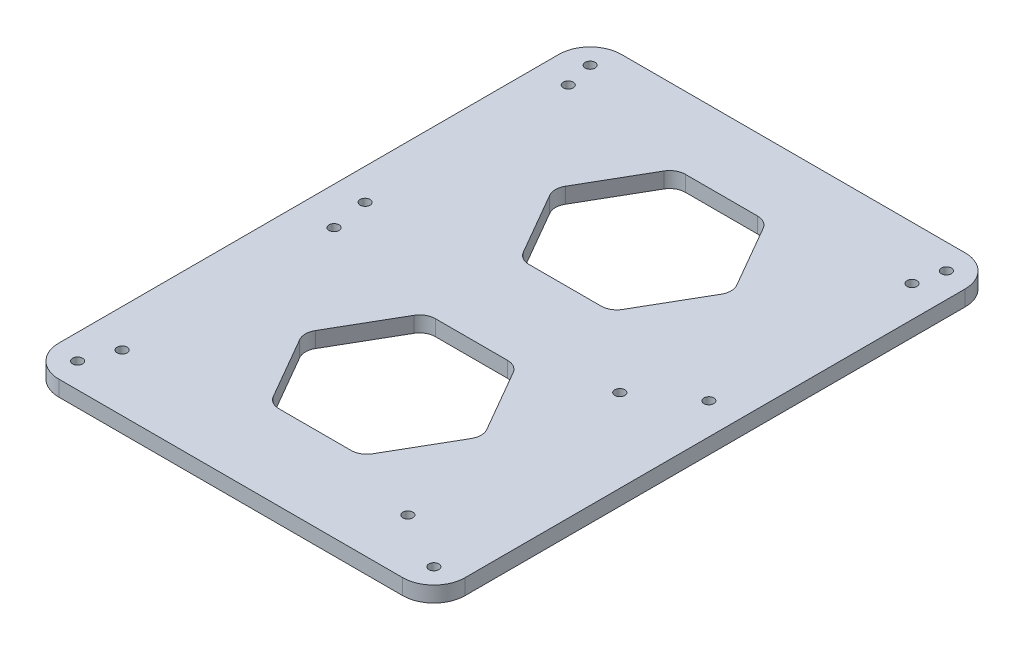
SolidWorks part; units mm, degrees
ref_plane "Front Plane" through (0, 0, 0) normal (0, 0, 1) x (1, 0, 0)
ref_plane "Top Plane" through (0, 0, 0) normal (0, 1, 0) x (1, 0, 0)
ref_plane "Right Plane" through (0, 0, 0) normal (1, 0, 0) x (0, 0, -1)
sketch "Sketch1" plane through (0, 0, 0) normal (0, 1, 0) x (1, 0, 0)
  line L0 (0, 0.2) -> (0, -76) construction
  line L1 (-65, 90) -> (65, 90)
  line L2 (-65, 90) -> (-65, -90)
  line L3 (-65, -90) -> (65, -90)
  line L4 (65, 90) -> (65, -90)
  line L5 (-65, 90) -> (65, -90) construction
  line L6 (-65, -90) -> (65, 90) construction
  line L7 (-58.42, 0.2) -> (58.42, 0.2)
  line L8 (-58.42, 0.2) -> (-58.42, -76)
  line L9 (-58.42, -76) -> (58.42, -76)
  line L10 (58.42, 0.2) -> (58.42, -76)
  line L11 (-58.42, 0.2) -> (58.42, -76) construction
  line L12 (-58.42, -76) -> (58.42, 0.2) construction
  line L13 (0, 90) -> (0, -90) construction
  line L15 (-60, 78) -> (60, 78)
  line L16 (-60, 78) -> (-60, 3)
  line L17 (-60, 3) -> (60, 3)
  line L18 (60, 78) -> (60, 3)
  line L19 (-60, 78) -> (60, 3) construction
  line L20 (-60, 3) -> (60, 78) construction
  circle A0 centre (-57, 82) radius 1.6
  circle A1 centre (57, 82) radius 1.6
  circle A2 centre (-57, -82) radius 1.6
  circle A3 centre (57, -82) radius 1.6
  circle A4 centre (38.48, -3.99) radius 1.6
  circle A5 centre (38.48, -71.81) radius 1.6
  circle A6 centre (-52.96, -3.99) radius 1.6
  circle A7 centre (-52.96, -71.81) radius 1.6
  circle A8 centre (-55, 73) radius 1.6
  circle A9 centre (-55, 8) radius 1.6
  circle A10 centre (55, 73) radius 1.6
  circle A11 centre (55, 8) radius 1.6
  point P0 (0, 0)
  point P14 (0, -37.9)
  point P31 (0, 40.5)
  dimension "D3" = 3.2
  dimension "D5" = 8
  dimension "D6" = 3.2
  dimension "D7" = 8
  dimension "D9" = 3.2
  dimension "D10" = 3.2
  dimension "D11" = 8
  dimension "D12" = 8
  dimension "D13" = 8
  dimension "D19" = 4.19
  dimension "D20" = 3.2
  dimension "D21" = 3.2
  dimension "D22" = 19.94
  dimension "D23" = 19.94
  dimension "D24" = 4.19
  dimension "D25" = 3.2
  dimension "D26" = 3.2
  dimension "D27" = 4.19
  dimension "D28" = 5.46
  dimension "D29" = 5.46
  dimension "D30" = 4.19
  dimension "D34" = 3.2
  dimension "D35" = 5
  dimension "D36" = 5
  dimension "D37" = 3.2
  dimension "D38" = 5
  dimension "D39" = 5
  dimension "D40" = 3.2
  dimension "D41" = 3.2
  dimension "D42" = 5
  dimension "D43" = 5
  dimension "D44" = 5
  dimension "D45" = 5
  dimension "D1" = 130
  dimension "D2" = 180
  dimension "D4" = 8
  dimension "D8" = 8
  dimension "D14" = 8
  dimension "D15" = 116.84
  dimension "D16" = 76.2
  dimension "D17" = 0
  dimension "D18" = 14
  dimension "D31" = 120
  dimension "D32" = 75
  dimension "D33" = 12
extrude "Boss-Extrude1" add sketch "Sketch1" along normal blind 5 contours L4 L1 L2 L3 A3 A2 A1 A0 L7 L10 L9 L8 L15 L18 L17 L16 | L18 L15 L16 L17 A11 A10 A9 A8 | L10 L7 L8 L9 A7 A6 A5 A4
fillet "Fillet1" radius 10 4 edges at (65, 2.5, 90) (65, 2.5, -90) (-65, 2.5, -90) (-65, 2.5, 90)
sketch "Sketch2" plane through (0, 5, 0) normal (0, 1, 0) x (1, 0, 0)
  line L0 (0, 0) -> (0, 42) construction
  line L1 (28.8675, 42) -> (14.4338, 67)
  line L2 (14.4338, 67) -> (-14.4338, 67)
  line L3 (-14.4338, 67) -> (-28.8675, 42)
  line L4 (-28.8675, 42) -> (-14.4338, 17)
  line L5 (-14.4338, 17) -> (14.4338, 17)
  line L6 (14.4338, 17) -> (28.8675, 42)
  line L8 (28.8675, -38) -> (14.4338, -13)
  line L9 (14.4338, -13) -> (-14.4338, -13)
  line L10 (-14.4338, -13) -> (-28.8675, -38)
  line L11 (-28.8675, -38) -> (-14.4338, -63)
  line L12 (-14.4338, -63) -> (14.4338, -63)
  line L13 (14.4338, -63) -> (28.8675, -38)
  circle A0 centre (0, 42) radius 25 construction
  circle A1 centre (0, -38) radius 25 construction
  dimension "D1" = 50
  dimension "D2" = 42
  dimension "D3" = 38
  dimension "D4" = 50
extrude "Cut-Extrude1" cut sketch "Sketch2" against normal blind 10 contours L1 L2 L3 L4 L5 L6 | L8 L9 L10 L11 L12 L13
fillet "Fillet2" radius 5 12 edges at (-14.4338, 2.5, 63) (-28.8675, 2.5, 38) (14.4338, 2.5, 63) (28.8675, 2.5, 38) (14.4338, 2.5, 13) (-14.4338, 2.5, 13) (14.4338, 2.5, -17) (-14.4338, 2.5, -17) (-28.8675, 2.5, -42) (-14.4338, 2.5, -67) (14.4338, 2.5, -67) (28.8675, 2.5, -42)
